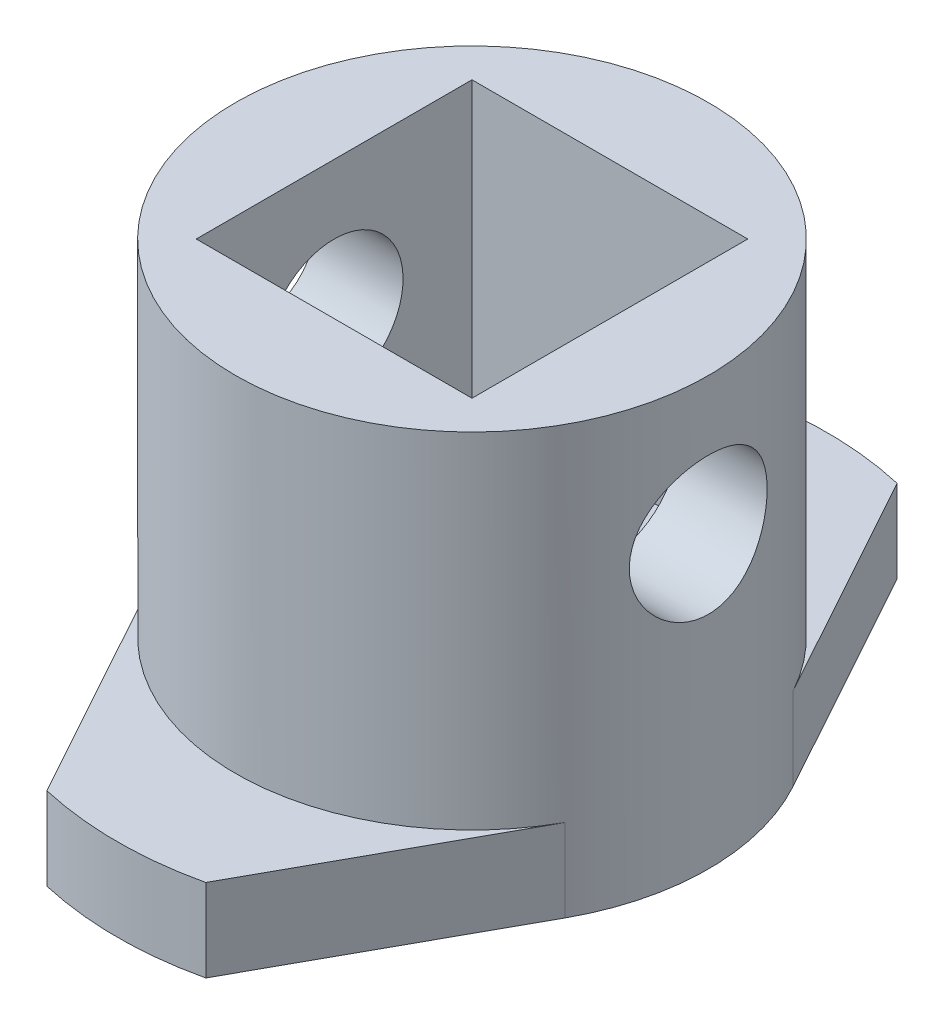
SolidWorks part; units mm, degrees
ref_plane "Alzado" through (0, 0, 0) normal (0, 0, 1) x (1, 0, 0)
ref_plane "Planta" through (0, 0, 0) normal (0, 1, 0) x (1, 0, 0)
ref_plane "Vista lateral" through (0, 0, 0) normal (1, 0, 0) x (0, 0, -1)
sketch "Croquis1" plane through (0, 0, 0) normal (0, 1, 0) x (1, 0, 0)
  line L0 (0, 22.0285) -> (0, -21.9539) construction
  line L1 (-30.488, 0) -> (37.573, 0) construction
  line L6 (-6.0081, 3.311) -> (-2.3063, 10.0282)
  line L7 (6.0081, 3.311) -> (2.3063, 10.0282)
  line L8 (6.0081, -3.311) -> (2.3063, -10.0282)
  line L9 (-6.0081, -3.311) -> (-2.3063, -10.0282)
  arc A0 (-6.0081, 3.311) -> (-6.0081, -3.311) centre (0, 0) ccw
  arc A1 (-2.3063, -10.0282) -> (2.3063, -10.0282) centre (0, 0) ccw
  arc A2 (2.3063, 10.0282) -> (-2.3063, 10.0282) centre (0, 0) ccw
  arc A3 (6.0081, -3.311) -> (6.0081, 3.311) centre (0, 0) ccw
  dimension "D1" = 13.72
  dimension "D2" = 20.58
  dimension "D3" = 25.904
  dimension "D4" = 25.904
  dimension "D5" = 10.0282
  dimension "D6" = 10.0282
extrude "Saliente-Extruir1" add sketch "Croquis1" along normal blind 2.4
sketch "Croquis2" plane through (0, 2.4, 0) normal (0, 1, 0) x (1, 0, 0)
  circle A0 centre (0, 0) radius 6.86
extrude "Saliente-Extruir2" add sketch "Croquis2" along normal blind 10
sketch "Croquis3" plane through (0, 12.4, 0) normal (0, 1, 0) x (1, 0, 0)
  line L1 (-4, 4) -> (4, 4)
  line L2 (-4, 4) -> (-4, -4)
  line L3 (-4, -4) -> (4, -4)
  line L4 (4, 4) -> (4, -4)
  line L5 (-4, 4) -> (4, -4) construction
  line L6 (-4, -4) -> (4, 4) construction
  point P0 (0, 0)
  dimension "D1" = 8
  dimension "D2" = 8
extrude "Cortar-Extruir1" cut sketch "Croquis3" against normal blind 8
sketch "Croquis5" plane through (-4, 0, 0) normal (1, 0, 0) x (0, 0, -1)
  line L0 (0, 13.8358) -> (0, -2.0541) construction
  line L1 (-11.397, 8.4) -> (12.0565, 8.4) construction
  line L2 (-4, 12.4) -> (4, 12.4) construction
  circle A0 centre (0, 8.4) radius 2
  dimension "D2" = 4
  dimension "D1" = 4
extrude "Cortar-Extruir2" cut sketch "Croquis5" against normal through all both and the other way through all
